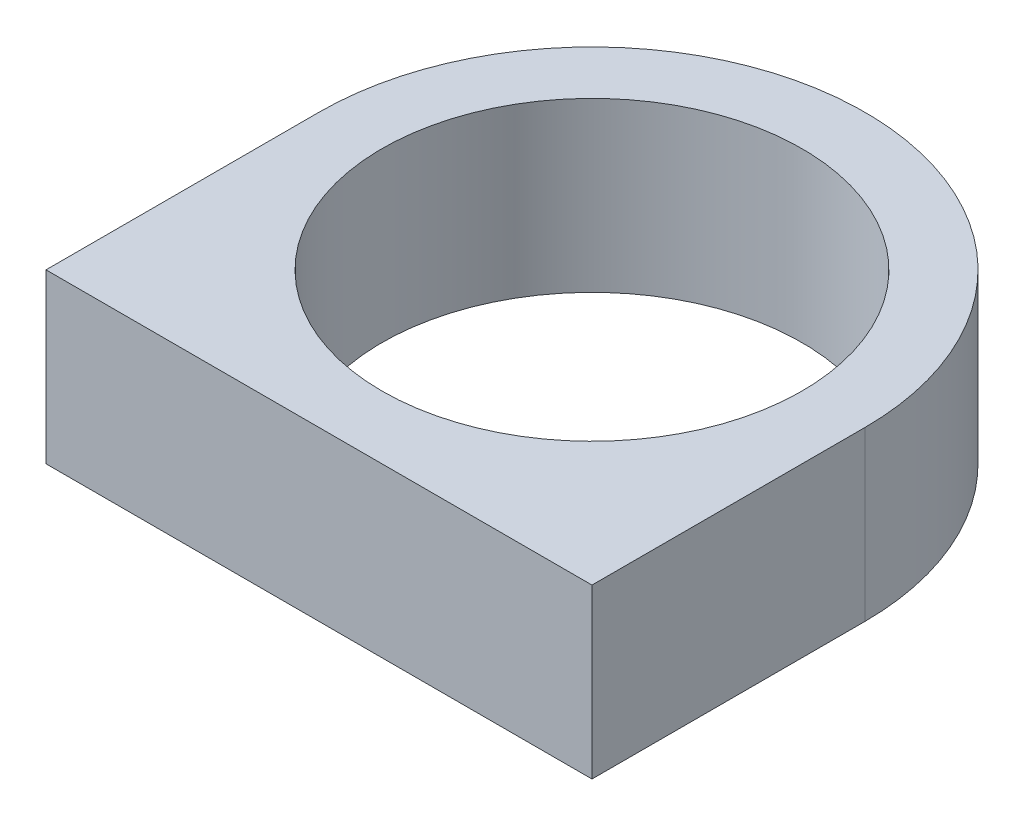
SolidWorks part; units mm, degrees
ref_plane "Front Plane" through (0, 0, 0) normal (0, 0, 1) x (1, 0, 0)
ref_plane "Top Plane" through (0, 0, 0) normal (0, 1, 0) x (1, 0, 0)
ref_plane "Right Plane" through (0, 0, 0) normal (1, 0, 0) x (0, 0, -1)
sketch "Sketch1" plane through (0, 0, 0) normal (0, 1, 0) x (1, 0, 0)
  line L0 (-3.25, 0) -> (-3.25, -3.25)
  line L1 (-3.25, -3.25) -> (3.25, -3.25)
  line L2 (3.25, -3.25) -> (3.25, 0)
  circle A0 centre (0, 0) radius 2.5
  arc A1 (3.25, 0) -> (-3.25, 0) centre (0, 0) ccw
  dimension "D1" = 5
  dimension "D2" = 6.5
extrude "Boss-Extrude1" add sketch "Sketch1" along normal blind 2
